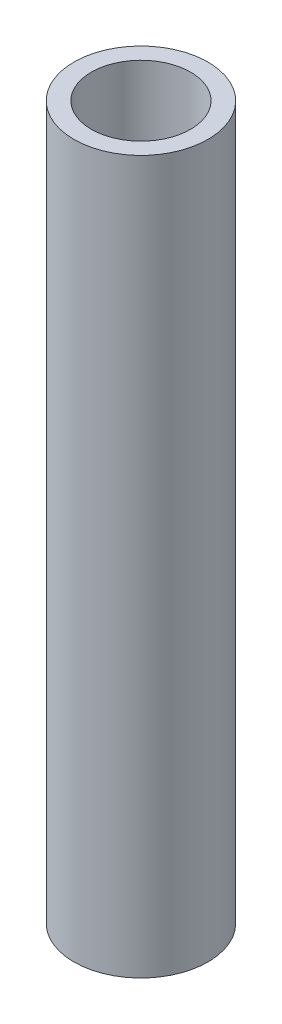
SolidWorks part; units mm, degrees
material "6061-T6 (SS)"
ref_plane "Front Plane" through (0, 0, 0) normal (0, 0, 1) x (1, 0, 0)
ref_plane "Top Plane" through (0, 0, 0) normal (0, 1, 0) x (1, 0, 0)
ref_plane "Right Plane" through (0, 0, 0) normal (1, 0, 0) x (0, 0, -1)
sketch "Sketch1" plane through (0, 0, 0) normal (0, 1, 0) x (1, 0, 0)
  circle A0 centre (0, 0) radius 12.7
  circle A1 centre (0, 0) radius 9.398
  dimension "D1" = 25.4
  dimension "D2" = 3.302
extrude "Boss-Extrude1" add sketch "Sketch1" along normal blind 135
